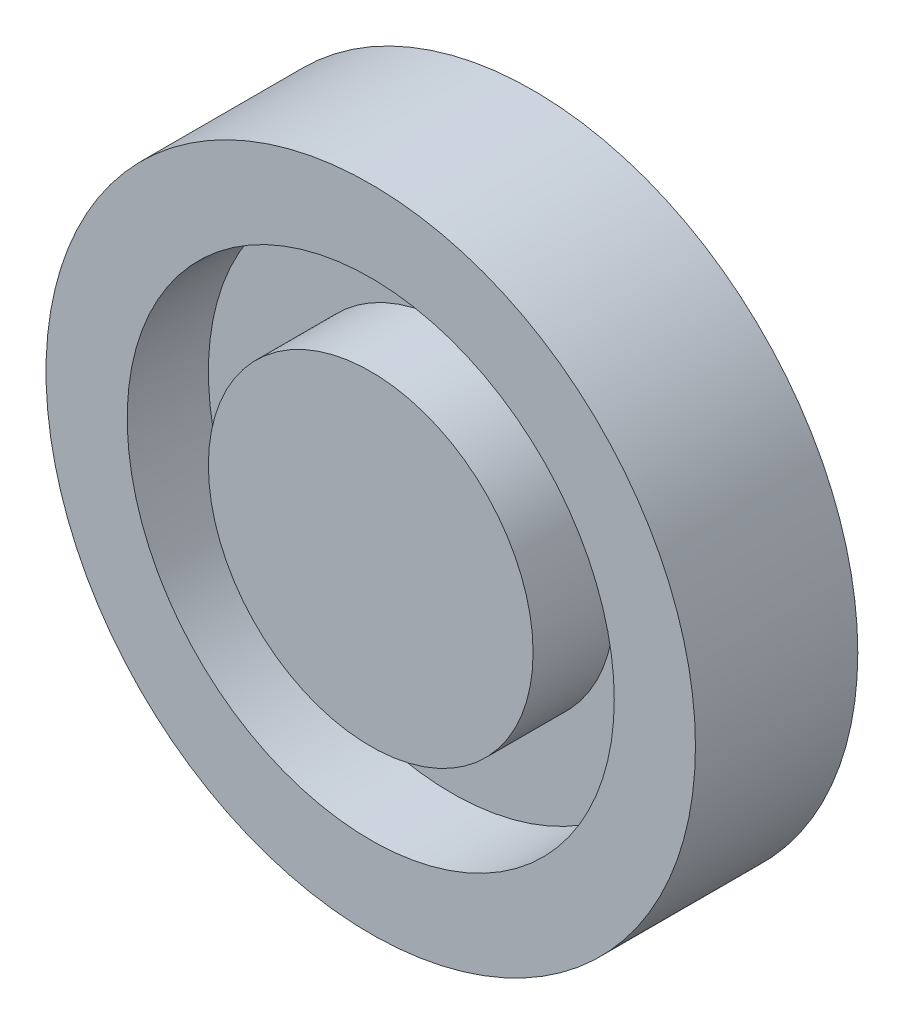
SolidWorks part; units mm, degrees
ref_plane "Front Plane" through (0, 0, 0) normal (0, 0, 1) x (1, 0, 0)
ref_plane "Top Plane" through (0, 0, 0) normal (0, 1, 0) x (1, 0, 0)
ref_plane "Right Plane" through (0, 0, 0) normal (1, 0, 0) x (0, 0, -1)
sketch "Sketch1" plane through (0, 0, 0) normal (0, 0, 1) x (1, 0, 0)
  circle A0 centre (0, 0) radius 2
extrude "Boss-Extrude1" add sketch "Sketch1" along normal blind 1
sketch "Sketch2" plane through (0, 0, 1) normal (0, 0, 1) x (1, 0, 0)
  circle A0 centre (0, 0) radius 1
  circle A1 centre (0, 0) radius 1.5
extrude "Cut-Extrude2" cut sketch "Sketch2" against normal blind 0.5
